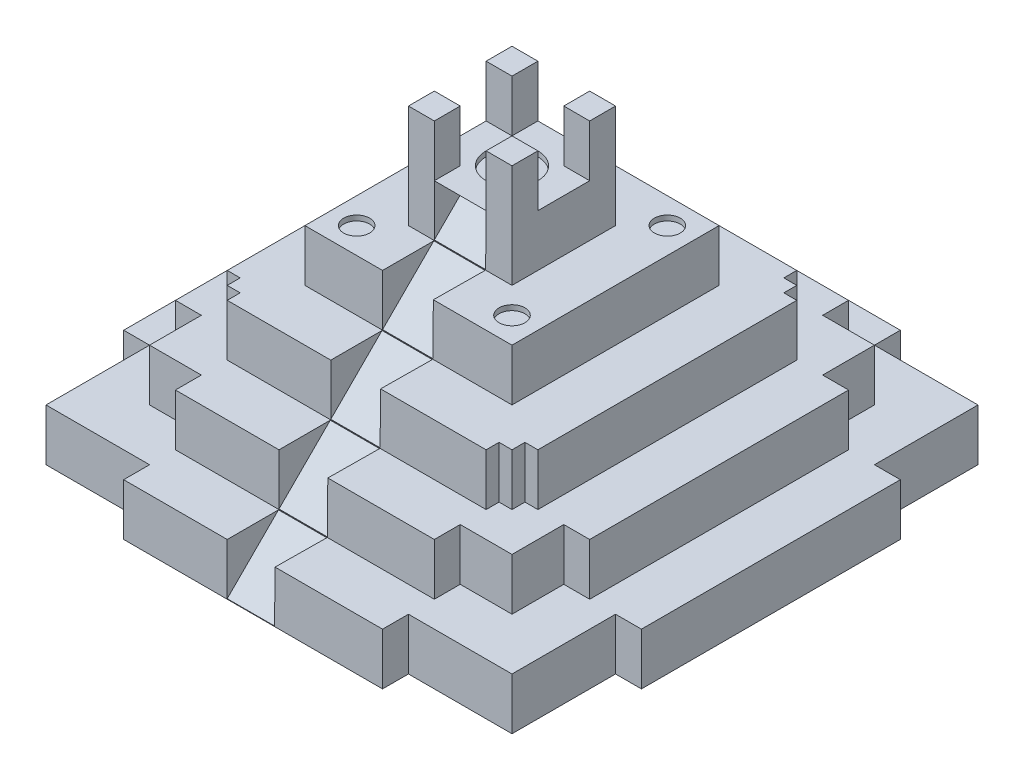
SolidWorks part; units mm, degrees
ref_plane "Front Plane" through (0, 0, 0) normal (0, 0, 1) x (1, 0, 0)
ref_plane "Top Plane" through (0, 0, 0) normal (0, 1, 0) x (1, 0, 0)
ref_plane "Right Plane" through (0, 0, 0) normal (1, 0, 0) x (0, 0, -1)
sketch "Sketch2" plane through (0, 0, 0) normal (0, 1, 0) x (1, 0, 0)
  line L0 (0, 0) -> (0, 1000)
  line L1 (0, 1000) -> (1000, 1000)
  line L2 (1000, 1000) -> (1000, 0)
  line L3 (1000, 0) -> (0, 0)
  dimension "D1" = 1000
  dimension "D2" = 1000
extrude "Boss-Extrude1" add sketch "Sketch2" along normal blind 100
sketch "Sketch3" plane through (0, 100, 0) normal (0, 1, 0) x (1, 0, 0)
  line L0 (100, 900) -> (100, 100)
  line L1 (100, 100) -> (900, 100)
  line L2 (900, 100) -> (900, 900)
  line L3 (900, 900) -> (100, 900)
  line L4 (0, 1000) -> (0, 0) construction
  line L5 (1000, 1000) -> (0, 1000) construction
  line L7 (0, 0) -> (1000, 0) construction
  line L8 (1000, 0) -> (1000, 1000) construction
  dimension "D1" = 100
  dimension "D2" = 100
  dimension "D3" = 100
  dimension "D4" = 100
extrude "Boss-Extrude2" add sketch "Sketch3" along normal blind 100
sketch "Sketch4" plane through (0, 200, 0) normal (0, 1, 0) x (1, 0, 0)
  line L0 (200, 800) -> (200, 200)
  line L1 (200, 200) -> (800, 200)
  line L2 (800, 200) -> (800, 800)
  line L3 (800, 800) -> (200, 800)
  line L4 (100, 900) -> (100, 100) construction
  line L5 (900, 100) -> (900, 900) construction
  line L6 (900, 900) -> (100, 900) construction
  line L7 (100, 100) -> (900, 100) construction
  dimension "D1" = 100
  dimension "D2" = 100
  dimension "D3" = 100
  dimension "D4" = 100
extrude "Boss-Extrude3" add sketch "Sketch4" along normal blind 100
sketch "Sketch5" plane through (0, 300, 0) normal (0, 1, 0) x (1, 0, 0)
  line L0 (300, 700) -> (300, 300)
  line L1 (300, 300) -> (700, 300)
  line L2 (700, 300) -> (700, 700)
  line L3 (700, 700) -> (300, 700)
  line L4 (800, 800) -> (200, 800) construction
  line L5 (200, 200) -> (800, 200) construction
  line L6 (800, 200) -> (800, 800) construction
  line L7 (200, 800) -> (200, 200) construction
  dimension "D1" = 100
  dimension "D2" = 100
  dimension "D3" = 100
  dimension "D4" = 100
extrude "Boss-Extrude4" add sketch "Sketch5" along normal blind 100
sketch "Sketch6" plane through (0, 400, 0) normal (0, 1, 0) x (1, 0, 0)
  line L0 (400, 600) -> (400, 400)
  line L1 (400, 400) -> (600, 400)
  line L2 (600, 400) -> (600, 600)
  line L3 (600, 600) -> (400, 600)
  line L4 (300, 700) -> (300, 300) construction
  line L5 (700, 300) -> (700, 700) construction
  line L6 (700, 700) -> (300, 700) construction
  line L7 (300, 300) -> (700, 300) construction
  dimension "D1" = 100
  dimension "D2" = 100
  dimension "D3" = 100
  dimension "D4" = 100
extrude "Boss-Extrude5" add sketch "Sketch6" along normal blind 100
sketch "Sketch8" plane through (0, 100, 0) normal (0, 1, 0) x (1, 0, 0)
  line L0 (0, 250) -> (250, 250)
  line L1 (0, 1000) -> (0, 0) construction
  line L2 (250, 250) -> (250, 0)
  line L3 (0, 0) -> (1000, 0) construction
  line L4 (250, 0) -> (0, 0)
  line L5 (0, 0) -> (0, 250)
  line L6 (500, 1000) -> (500, -43.4954) construction
  line L7 (1000, 1000) -> (0, 1000) construction
  line L8 (0, 500) -> (1088.8261, 500) construction
  line L9 (750, 250) -> (750, 0)
  line L10 (750, 0) -> (1000, 0)
  line L11 (1000, 0) -> (1000, 250)
  line L12 (1000, 250) -> (750, 250)
  line L13 (1000, 750) -> (750, 750)
  line L14 (1000, 1000) -> (1000, 750)
  line L15 (750, 1000) -> (1000, 1000)
  line L16 (750, 750) -> (750, 1000)
  line L17 (0, 1000) -> (0, 750)
  line L18 (250, 1000) -> (0, 1000)
  line L19 (250, 750) -> (250, 1000)
  line L20 (0, 750) -> (250, 750)
  dimension "D1" = 250
  dimension "D2" = 250
extrude "Cut-Extrude2" cut sketch "Sketch8" along normal through all both and the other way through all
sketch "Sketch9" plane through (0, 500, 0) normal (0, 1, 0) x (1, 0, 0)
  line L0 (500, 400) -> (500, -70.9678) construction
  line L1 (400, 400) -> (600, 400) construction
  line L2 (450, 400) -> (550, 400)
  line L3 (400, 400) -> (600, 400) construction
  point P8 (500, 400)
  point P10 (550, 199.3227)
  point P12 (500, -70.9678)
  dimension "D1" = 100
sketch "Sketch10" plane through (0, 500, 0) normal (0, 1, 0) x (1, 0, 0)
  line L0 (550, 400) -> (550, -52.6528) construction
  line L1 (450, 400) -> (450, -36.1694) construction
  line L2 (250, 200) -> (750, 200) construction
  point P0 (450, 400)
  point P1 (550, 400)
  point P8 (450, 200)
  point P9 (550, 199.3227)
sketch "Sketch11" plane through (0, 100, 0) normal (0, 1, 0) x (1, 0, 0)
  line L0 (450, 400) -> (450, -36.1694) construction
  line L1 (550, 400) -> (550, -52.6528) construction
  line L2 (250, 0) -> (750, 0) construction
  line L3 (250, 100) -> (750, 100) construction
  line L4 (500, 400) -> (500, -70.9678) construction
  point P0 (450, 0)
  point P1 (550, 0)
  point P4 (450, 100)
  point P9 (550, 100)
  dimension "D1" = 50
  dimension "D2" = 50
ref_plane "Plane2" through (0, 50, 50) normal (0, 0.7071, 0.7071) x (1, 0, 0)
sketch "Sketch16" plane through (0, 50, 50) normal (0, 0.7071, 0.7071) x (1, 0, 0)
  line L0 (450, 636.3961) -> (450, -32.3666)
  line L1 (450, -32.3666) -> (540.9638, -32.3666)
  line L2 (540.9638, -32.3666) -> (550, 636.3961)
  line L3 (400, 636.3961) -> (600, 636.3961) construction
  line L4 (550, 636.3961) -> (450, 636.3961)
extrude "Cut-Extrude3" cut sketch "Sketch16" against normal blind 70 and the other way through all
sketch "Sketch17" plane through (0, 0, 0) normal (0, 1, 0) x (1, 0, 0)
  line L0 (50, 750) -> (50, 950)
  line L1 (0, 750) -> (100, 750) construction
  line L2 (50, 950) -> (250, 950)
  line L3 (250, 900) -> (250, 1000) construction
  line L4 (250, 950) -> (250, 750)
  line L5 (250, 750) -> (50, 750)
  line L6 (500, 1000) -> (500, -130.2995) construction
  line L7 (750, 1000) -> (250, 1000) construction
  line L8 (100, 500) -> (1149.2464, 500) construction
  line L9 (100, 750) -> (100, 250) construction
  line L10 (750, 950) -> (750, 750)
  line L11 (950, 950) -> (750, 950)
  line L12 (950, 750) -> (950, 950)
  line L13 (750, 750) -> (950, 750)
  line L14 (950, 50) -> (750, 50)
  line L15 (950, 250) -> (950, 50)
  line L16 (750, 250) -> (950, 250)
  line L17 (750, 50) -> (750, 250)
  line L18 (50, 250) -> (50, 50)
  line L19 (250, 250) -> (50, 250)
  line L20 (250, 50) -> (250, 250)
  line L21 (50, 50) -> (250, 50)
  dimension "D1" = 200
extrude "Boss-Extrude6" add sketch "Sketch17" along normal blind 100
sketch "Sketch18" plane through (0, 100, 0) normal (0, 1, 0) x (1, 0, 0)
  line L0 (150, 250) -> (150, 150)
  line L1 (100, 250) -> (200, 250) construction
  line L2 (150, 150) -> (250, 150)
  line L3 (250, 100) -> (250, 250) construction
  line L4 (250, 150) -> (250, 250)
  line L5 (250, 250) -> (150, 250)
  line L6 (400, 500) -> (1449.0482, 500) construction
  line L7 (400, 600) -> (400, 400) construction
  line L8 (500, 1000) -> (500, -242.0321) construction
  line L9 (750, 1000) -> (250, 1000) construction
  line L10 (750, 150) -> (750, 250)
  line L11 (850, 150) -> (750, 150)
  line L12 (850, 250) -> (850, 150)
  line L13 (750, 250) -> (850, 250)
  line L14 (850, 850) -> (750, 850)
  line L15 (850, 750) -> (850, 850)
  line L16 (750, 750) -> (850, 750)
  line L17 (750, 850) -> (750, 750)
  line L18 (150, 750) -> (150, 850)
  line L19 (250, 750) -> (150, 750)
  line L20 (250, 850) -> (250, 750)
  line L21 (150, 850) -> (250, 850)
  dimension "D1" = 100
extrude "Boss-Extrude7" add sketch "Sketch18" along normal blind 100
sketch "Sketch19" plane through (0, 200, 0) normal (0, 1, 0) x (1, 0, 0)
  line L0 (750, 225) -> (775, 225)
  line L1 (750, 200) -> (750, 250) construction
  line L2 (775, 225) -> (775, 250)
  line L4 (750, 250) -> (800, 250) construction
  line L5 (775, 250) -> (750, 250)
  line L6 (750, 250) -> (750, 225)
  line L7 (500, 900) -> (500, -112.2075) construction
  line L8 (750, 900) -> (250, 900) construction
  line L9 (100, 500) -> (1374.498, 500) construction
  line L10 (100, 750) -> (100, 250) construction
  line L11 (775, 750) -> (750, 750)
  line L12 (775, 775) -> (775, 750)
  line L13 (750, 775) -> (775, 775)
  line L14 (750, 750) -> (750, 775)
  line L15 (225, 775) -> (225, 750)
  line L16 (250, 775) -> (225, 775)
  line L17 (250, 750) -> (250, 775)
  line L18 (225, 750) -> (250, 750)
  line L19 (250, 225) -> (225, 225)
  line L20 (250, 250) -> (250, 225)
  line L21 (225, 250) -> (250, 250)
  line L22 (225, 225) -> (225, 250)
  dimension "D1" = 25
  dimension "D2" = 25
extrude "Boss-Extrude8" add sketch "Sketch19" along normal blind 100
sketch "Sketch20" plane through (0, 500, 0) normal (0, 1, 0) x (1, 0, 0)
  line L0 (450, 600) -> (450, 550)
  line L1 (600, 600) -> (400, 600) construction
  line L2 (450, 550) -> (400, 550)
  line L3 (400, 600) -> (400, 400) construction
  line L4 (400, 550) -> (400, 600)
  line L5 (400, 600) -> (450, 600)
  line L6 (500, 600) -> (500, -226.6331) construction
  line L7 (600, 600) -> (400, 600) construction
  line L8 (400, 500) -> (1257.5071, 500) construction
  line L9 (400, 450) -> (400, 400)
  line L10 (450, 450) -> (400, 450)
  line L11 (450, 400) -> (450, 450)
  line L12 (400, 400) -> (450, 400)
  line L13 (550, 450) -> (600, 450)
  line L14 (550, 400) -> (550, 450)
  line L15 (600, 400) -> (550, 400)
  line L16 (600, 450) -> (600, 400)
  line L17 (550, 600) -> (550, 550)
  line L18 (600, 600) -> (550, 600)
  line L19 (600, 550) -> (600, 600)
  line L20 (550, 550) -> (600, 550)
  dimension "D1" = 50
  dimension "D2" = 50
extrude "Boss-Extrude9" add sketch "Sketch20" along normal blind 100
sketch "Sketch21" plane through (0, 500, 0) normal (0, 1, 0) x (1, 0, 0)
  line L0 (600, 450) -> (600, 550) construction
  line L2 (450, 400) -> (550, 400) construction
  circle A0 centre (500, 500) radius 50
  point P4 (600, 500)
  dimension "D3" = 100
  dimension "D1" = 100
  dimension "D2" = 100
extrude "Cut-Extrude4" cut sketch "Sketch21" against normal blind 10 contours A0
sketch "Sketch22" plane through (0, 400, 0) normal (0, 1, 0) x (1, 0, 0)
  line L0 (700, 700) -> (300, 700) construction
  line L1 (300, 700) -> (300, 300) construction
  line L2 (500, 800) -> (500, -108.7233) construction
  line L3 (750, 800) -> (250, 800) construction
  line L4 (200, 500) -> (1219.8593, 500) construction
  line L5 (200, 750) -> (200, 250) construction
  circle A0 centre (350, 650) radius 25
  circle A1 centre (650, 650) radius 25
  circle A2 centre (650, 350) radius 25
  circle A3 centre (350, 350) radius 25
  dimension "D3" = 50
  dimension "D1" = 50
  dimension "D2" = 50
extrude "Cut-Extrude5" cut sketch "Sketch22" against normal blind 10
